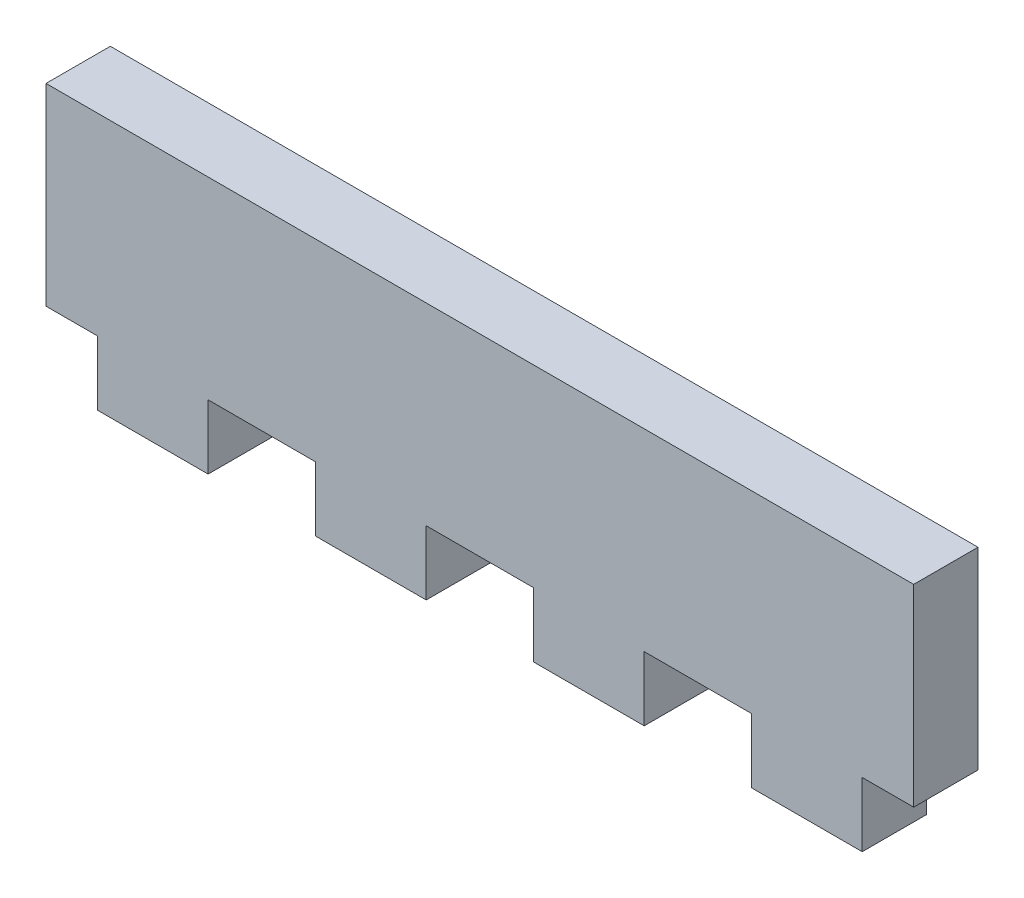
SolidWorks part; units mm, degrees
ref_plane "Front" through (0, 0, 0) normal (0, 0, 1) x (1, 0, 0)
ref_plane "Top" through (0, 0, 0) normal (0, 1, 0) x (1, 0, 0)
ref_plane "Right" through (0, 0, 0) normal (1, 0, 0) x (0, 0, -1)
sketch "Sketch1" plane through (0, 0, 0) normal (0, 0, 1) x (1, 0, 0)
  line L0 (5.7356, 29.8612) -> (-2.8651, 29.8612)
  line L1 (-11.2119, 29.8612) -> (-19.8161, 29.8612)
  line L2 (-28.1628, 29.8612) -> (-36.7671, 29.8612)
  line L3 (-28.1628, 29.8612) -> (-28.1628, 34.8612)
  line L4 (-19.8161, 29.8612) -> (-19.8161, 34.8612)
  line L5 (-19.8161, 34.8612) -> (-28.1628, 34.8612)
  line L6 (-11.2119, 29.8612) -> (-11.2119, 34.8612)
  line L7 (-11.2119, 34.8612) -> (-2.8651, 34.8612)
  line L8 (-2.8651, 34.8612) -> (-2.8651, 29.8612)
  line L9 (5.7356, 29.8612) -> (5.7356, 34.8612)
  line L10 (22.6831, 29.8612) -> (14.0824, 29.8612)
  line L11 (-36.7671, 29.8612) -> (-36.7671, 34.8612)
  line L12 (-36.7671, 34.8612) -> (-40.7671, 34.8612)
  line L13 (5.7356, 34.8612) -> (14.0824, 34.8612)
  line L14 (-40.7671, 34.8612) -> (-40.7671, 49.8612)
  line L15 (14.0824, 34.8612) -> (14.0824, 29.8612)
  line L16 (22.6831, 29.8612) -> (22.6831, 34.8612)
  line L17 (22.6831, 34.8612) -> (26.6831, 34.8612)
  line L18 (26.6831, 34.8612) -> (26.6831, 49.8612)
  line L19 (26.6831, 49.8612) -> (-40.7671, 49.8612)
extrude "Boss-Extrude1" add sketch "Sketch1" along normal blind 5
